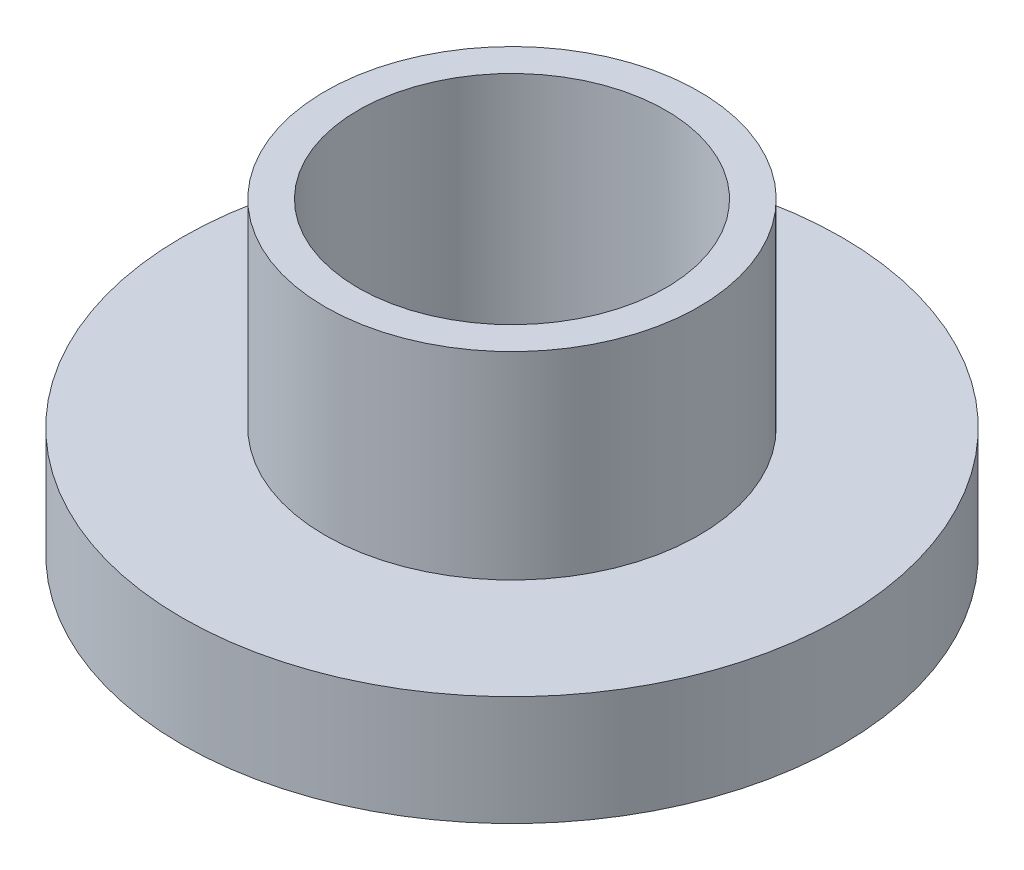
SolidWorks part; units mm, degrees
ref_plane "前视基准面" through (0, 0, 0) normal (0, 0, 1) x (1, 0, 0)
ref_plane "上视基准面" through (0, 0, 0) normal (0, 1, 0) x (1, 0, 0)
ref_plane "右视基准面" through (0, 0, 0) normal (1, 0, 0) x (0, 0, -1)
sketch "草图1" plane through (0, 0, 0) normal (0, 1, 0) x (1, 0, 0)
  line L0 (-14.6896, 0) -> (12.7218, 0) construction
  line L5 (0, 7.9866) -> (0, -8.1972) construction
  circle A0 centre (0, 0) radius 3
  dimension "D1" = 6
extrude "拉伸1" add sketch "草图1" along normal blind 2.8
sketch "草图2" plane through (0, 2.8, 0) normal (0, 1, 0) x (-1, 0, 0)
  circle A0 centre (0, 0) radius 1.4
  dimension "D1" = 2.8
extrude "切除-拉伸1" cut sketch "草图2" against normal through all
sketch "草图3" plane through (0, 2.8, 0) normal (0, 1, 0) x (1, 0, 0)
  circle A0 centre (0, 0) radius 1.7
  circle A2 centre (0, 0) radius 1.4 construction
  dimension "D1" = 0.3
extrude "切除-拉伸2" cut sketch "草图3" against normal offset from surface (1.8 mm away) 1 flip side to cut up to face at (0, 0, 1.4)
